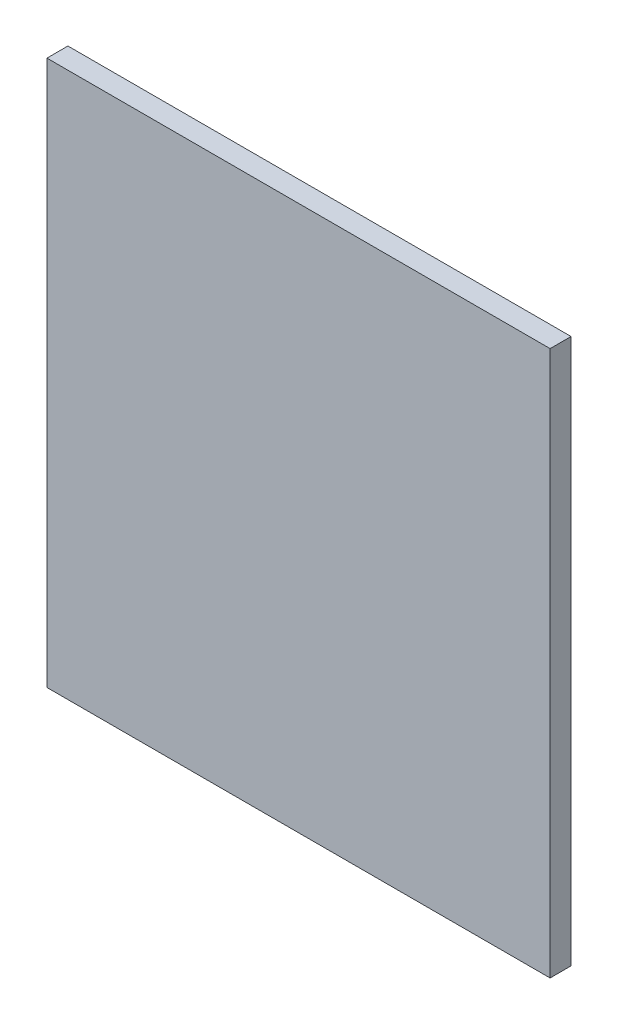
SolidWorks part; units mm, degrees
material "玻璃"
ref_plane "前基準面" through (0, 0, 0) normal (0, 0, 1) x (1, 0, 0)
ref_plane "上基準面" through (0, 0, 0) normal (0, 1, 0) x (1, 0, 0)
ref_plane "右基準面" through (0, 0, 0) normal (1, 0, 0) x (0, 0, -1)
sketch "草圖1" plane through (0, 0, 0) normal (0, 0, 1) x (1, 0, 0)
  line L1 (-6, 6.5) -> (6, 6.5)
  line L2 (-6, 6.5) -> (-6, -6.5)
  line L3 (-6, -6.5) -> (6, -6.5)
  line L4 (6, 6.5) -> (6, -6.5)
  line L5 (-6, 6.5) -> (6, -6.5) construction
  line L6 (-6, -6.5) -> (6, 6.5) construction
  point P0 (0, 0)
  dimension "D1" = 13
  dimension "D2" = 12
extrude "填料-伸長1" add sketch "草圖1" along normal blind 0.5
